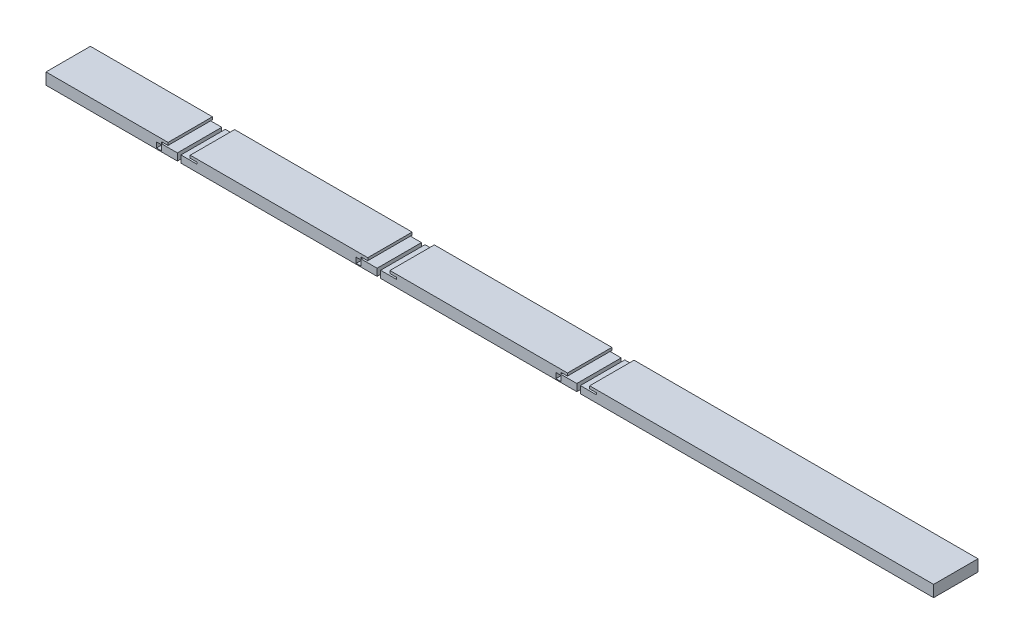
SolidWorks part; units mm, degrees
ref_plane "Front Plane" through (0, 0, 0) normal (0, 0, 1) x (1, 0, 0)
ref_plane "Top Plane" through (0, 0, 0) normal (0, 1, 0) x (1, 0, 0)
ref_plane "Right Plane" through (0, 0, 0) normal (1, 0, 0) x (0, 0, -1)
sketch "Sketch1" plane through (0, 0, 0) normal (0, 1, 0) x (1, 0, 0)
  line L1 (-21.3043, -8.2174) -> (178.6957, -8.2174)
  line L2 (-21.3043, -8.2174) -> (-21.3043, 1.7826)
  line L3 (-21.3043, 1.7826) -> (178.6957, 1.7826)
  line L4 (178.6957, -8.2174) -> (178.6957, 1.7826)
  dimension "D1" = 10
  dimension "D2" = 200
extrude "Boss-Extrude1" add sketch "Sketch1" along normal blind 2.6 contours L1 L4 L3 L2
sketch "Sketch3" plane through (0, 0, 0) normal (0, -1, 0) x (1, 0, 0)
  line L5 (-21.3043, 8.2174) -> (178.6957, 8.2174) construction
  line L6 (8.2957, 8.2174) -> (9.0957, 8.2174)
  line L7 (8.2957, 8.2174) -> (8.2957, -1.7826)
  line L8 (8.2957, -1.7826) -> (9.0957, -1.7826)
  line L9 (9.0957, 8.2174) -> (9.0957, -1.7826)
  line L10 (-21.3043, -1.7826) -> (178.6957, -1.7826) construction
  line L11 (-21.3043, 8.2174) -> (-21.3043, -1.7826) construction
  line L13 (53.2957, 8.2174) -> (54.0957, 8.2174)
  line L14 (53.2957, 8.2174) -> (53.2957, -1.7826)
  line L15 (53.2957, -1.7826) -> (54.0957, -1.7826)
  line L16 (54.0957, 8.2174) -> (54.0957, -1.7826)
  line L17 (98.2957, 8.2174) -> (99.0957, 8.2174)
  line L18 (98.2957, 8.2174) -> (98.2957, -1.7826)
  line L19 (98.2957, -1.7826) -> (99.0957, -1.7826)
  line L20 (99.0957, 8.2174) -> (99.0957, -1.7826)
  dimension "D1" = 0.8
  dimension "D2" = 29.6
  dimension "D3" = 0.8
  dimension "D4" = 44.2
  dimension "D5" = 0.8
  dimension "D6" = 44.2
extrude "Cut-Extrude1" cut sketch "Sketch3" against normal blind 2
sketch "Sketch4" plane through (0, 2.6, 0) normal (0, 1, 0) x (1, 0, 0)
  line L0 (-21.3043, 1.7826) -> (178.6957, 1.7826) construction
  line L5 (-21.3043, -8.2174) -> (178.6957, -8.2174) construction
  line L11 (101.1957, 1.7826) -> (96.1957, 1.7826)
  line L12 (101.1957, 1.7826) -> (101.1957, -8.2174)
  line L13 (101.1957, -8.2174) -> (96.1957, -8.2174)
  line L14 (96.1957, 1.7826) -> (96.1957, -8.2174)
  line L16 (51.1957, 1.7826) -> (56.1957, 1.7826)
  line L17 (51.1957, 1.7826) -> (51.1957, -8.2174)
  line L18 (51.1957, -8.2174) -> (56.1957, -8.2174)
  line L19 (56.1957, 1.7826) -> (56.1957, -8.2174)
  line L20 (6.1957, 1.7826) -> (11.1957, 1.7826)
  line L21 (6.1957, 1.7826) -> (6.1957, -8.2174)
  line L22 (6.1957, -8.2174) -> (11.1957, -8.2174)
  line L23 (11.1957, 1.7826) -> (11.1957, -8.2174)
  line L26 (-21.3043, -8.2174) -> (-21.3043, 1.7826) construction
  dimension "D2" = 40
  dimension "D3" = 27.5
  dimension "D5" = 5
  dimension "D7" = 5
  dimension "D8" = 5
  dimension "D10" = 40
extrude "Cut-Extrude2" cut sketch "Sketch4" against normal blind 0.6
sketch "Sketch5" plane through (0, 2, 0) normal (0, 1, 0) x (1, 0, 0)
  line L1 (96.1957, 1.7826) -> (101.1957, 1.7826)
  line L2 (96.1957, 1.7826) -> (96.1957, -8.2174)
  line L3 (96.1957, -8.2174) -> (101.1957, -8.2174)
  line L4 (101.1957, 1.7826) -> (101.1957, -8.2174)
  line L15 (51.1957, 1.7826) -> (56.1957, 1.7826)
  line L16 (51.1957, 1.7826) -> (51.1957, -8.2174)
  line L17 (51.1957, -8.2174) -> (56.1957, -8.2174)
  line L18 (56.1957, 1.7826) -> (56.1957, -8.2174)
  line L19 (6.1957, 1.7826) -> (11.1957, 1.7826)
  line L20 (6.1957, 1.7826) -> (6.1957, -8.2174)
  line L21 (6.1957, -8.2174) -> (11.1957, -8.2174)
  line L22 (11.1957, 1.7826) -> (11.1957, -8.2174)
extrude "Boss-Extrude2" add sketch "Sketch5" along normal blind 0.6 separate body
ref_plane "Plane1" through (0, 2, 0) normal (0, 1, 0) x (1, 0, 0)
sketch "Sketch6" plane through (0, 2, 0) normal (0, 1, 0) x (1, 0, 0)
  line L5 (-21.3043, -8.2174) -> (6.1957, -8.2174) construction
  line L6 (9.0957, 1.7826) -> (12.6957, 1.7826)
  line L33 (54.0957, 1.7826) -> (54.0957, -8.2174)
  line L37 (53.2957, 1.7826) -> (53.2957, -8.2174)
  line L46 (101.1957, 1.7826) -> (96.1957, 1.7826) construction
  line L48 (51.1957, 1.7826) -> (51.1957, -8.2174) construction
  line L50 (9.0957, 1.7826) -> (9.0957, -8.2174)
  line L51 (9.0957, -8.2174) -> (12.6957, -8.2174)
  line L52 (98.2957, 1.7826) -> (94.6957, 1.7826)
  line L78 (98.2957, 1.7826) -> (98.2957, -8.2174)
  line L81 (98.2957, -8.2174) -> (94.6957, -8.2174)
  line L84 (94.6957, 1.7826) -> (94.6957, -8.2174)
  line L87 (101.1957, -8.2174) -> (178.6957, -8.2174) construction
  line L94 (99.0957, 1.7826) -> (102.6957, 1.7826)
  line L99 (99.0957, 1.7826) -> (99.0957, -8.2174)
  line L102 (99.0957, -8.2174) -> (102.6957, -8.2174)
  line L105 (102.6957, 1.7826) -> (102.6957, -8.2174)
  line L112 (96.1957, 1.7826) -> (96.1957, -8.2174) construction
  line L121 (12.6957, 1.7826) -> (12.6957, -8.2174)
  line L122 (11.1957, 1.7826) -> (6.1957, 1.7826) construction
  line L123 (8.2957, 1.7826) -> (4.6957, 1.7826)
  line L124 (8.2957, 1.7826) -> (8.2957, -8.2174)
  line L125 (8.2957, -8.2174) -> (4.6957, -8.2174)
  line L126 (4.6957, 1.7826) -> (4.6957, -8.2174)
  line L127 (-21.3043, -8.2174) -> (6.1957, -8.2174) construction
  line L128 (6.1957, 1.7826) -> (6.1957, -8.2174) construction
  line L130 (56.1957, 1.7826) -> (96.1957, 1.7826) construction
  line L140 (54.0957, 1.7826) -> (57.6957, 1.7826)
  line L141 (57.6957, 1.7826) -> (57.6957, -8.2174)
  line L142 (56.1957, -8.2174) -> (96.1957, -8.2174) construction
  line L143 (57.6957, -8.2174) -> (54.0957, -8.2174)
  line L144 (53.2957, 1.7826) -> (49.6957, 1.7826)
  line L145 (-21.3043, 1.7826) -> (6.1957, 1.7826) construction
  line L146 (49.6957, 1.7826) -> (49.6957, -8.2174)
  line L147 (49.6957, -8.2174) -> (53.2957, -8.2174)
  dimension "D2" = 0.8
  dimension "D3" = 3.6
  dimension "D4" = 3.6
  dimension "D5" = 3.6
  dimension "D6" = 2.1
  dimension "D12" = 0.8
  dimension "D13" = 3.6
  dimension "D15" = 3.6
  dimension "D16" = 0.8
  dimension "D17" = 3.6
  dimension "D18" = 2.1
  dimension "D19" = 2.1
extrude "Cut-Extrude3" cut sketch "Sketch6" against normal blind 0.4
sketch "Sketch11" plane through (0, 0, 8.2174) normal (0, 0, 1) x (1, 0, 0)
  line L0 (96.1957, 2.6) -> (96.1957, 2) construction
  line L39 (51.1957, 2.6) -> (51.1957, 2) construction
  line L44 (6.1957, 2.6) -> (6.1957, 2) construction
  line L49 (4.6957, 1.4) -> (3.5957, 1.4)
  line L54 (4.6957, 1.4) -> (4.6957, 0.2)
  line L79 (4.6957, 0.2) -> (3.5957, 0.2)
  line L84 (3.5957, 1.4) -> (3.5957, 0.2)
  line L85 (-21.3043, 2.6) -> (6.1957, 2.6) construction
  line L94 (-21.3043, 2.6) -> (6.1957, 2.6) construction
  line L95 (56.1957, 2.6) -> (96.1957, 2.6) construction
  line L98 (48.5957, 1.4) -> (49.6957, 1.4)
  line L99 (48.5957, 1.4) -> (48.5957, 0.2)
  line L100 (48.5957, 0.2) -> (49.6957, 0.2)
  line L101 (49.6957, 1.4) -> (49.6957, 0.2)
  line L102 (93.5957, 1.4) -> (94.6957, 1.4)
  line L103 (93.5957, 1.4) -> (93.5957, 0.2)
  line L104 (93.5957, 0.2) -> (94.6957, 0.2)
  line L105 (94.6957, 1.4) -> (94.6957, 0.2)
  dimension "D2" = 1.1
  dimension "D3" = 1.5
  dimension "D4" = 1.1
  dimension "D5" = 1.5
  dimension "D9" = 1.1
  dimension "D10" = 1.5
  dimension "D12" = 1.2
  dimension "D13" = 1.2
  dimension "D14" = 1.2
  dimension "D15" = 1.2
  dimension "D18" = 1.2
  dimension "D19" = 1.2
extrude "Cut-Extrude4" cut sketch "Sketch11" against normal blind 5
sketch "Sketch12" plane through (0, 2.6, 0) normal (0, 1, 0) x (1, 0, 0)
  line L0 (11.1957, -8.2174) -> (11.1957, 1.7826) construction
  line L1 (6.1957, 1.7826) -> (11.1957, 1.7826)
  line L2 (6.1957, 1.7826) -> (6.1957, -8.2174)
  line L3 (6.1957, -8.2174) -> (11.1957, -8.2174)
  line L4 (11.1957, 1.7826) -> (11.1957, -8.2174)
  line L6 (51.1957, 1.7826) -> (56.1957, 1.7826)
  line L7 (51.1957, 1.7826) -> (51.1957, -8.2174)
  line L8 (51.1957, -8.2174) -> (56.1957, -8.2174)
  line L9 (56.1957, 1.7826) -> (56.1957, -8.2174)
  line L10 (96.1957, 1.7826) -> (101.1957, 1.7826)
  line L11 (96.1957, 1.7826) -> (96.1957, -8.2174)
  line L12 (96.1957, -8.2174) -> (101.1957, -8.2174)
  line L13 (101.1957, 1.7826) -> (101.1957, -8.2174)
extrude "Cut-Extrude6" cut sketch "Sketch12" against normal blind 0.6
